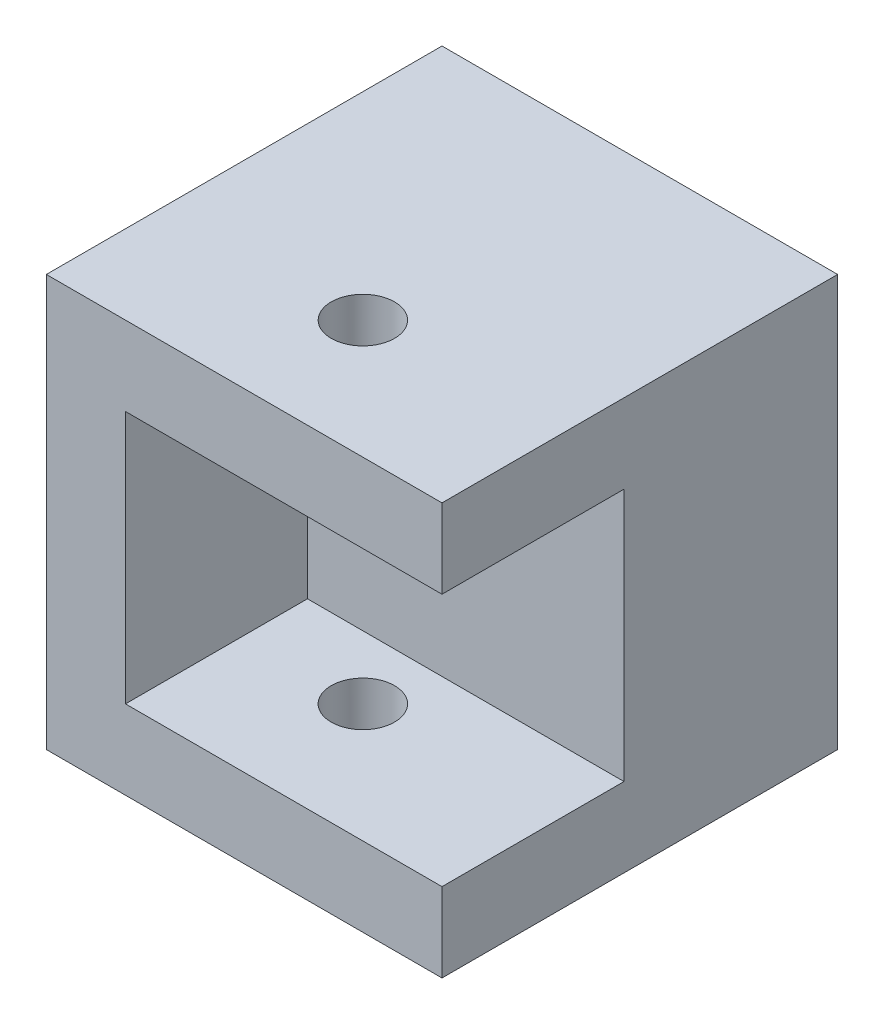
SolidWorks part; units mm, degrees
ref_plane "Front Plane" through (0, 0, 0) normal (0, 0, 1) x (1, 0, 0)
ref_plane "Top Plane" through (0, 0, 0) normal (0, 1, 0) x (1, 0, 0)
ref_plane "Right Plane" through (0, 0, 0) normal (1, 0, 0) x (0, 0, -1)
sketch "Sketch1" plane through (0, 0, 0) normal (0, 0, 1) x (1, 0, 0)
  line L0 (15.2003, 13.7604) -> (0.2003, 13.7604)
  line L1 (-4.7997, -6.2396) -> (0.2003, -6.2396)
  line L2 (-4.7997, -6.2396) -> (-4.7997, 19.7604)
  line L3 (-4.7997, 19.7604) -> (15.2003, 19.7604)
  line L4 (15.2003, 13.7604) -> (15.2003, 19.7604)
  line L5 (-4.7997, -6.2396) -> (15.2003, 19.7604) construction
  line L6 (-4.7997, 19.7604) -> (0, 0) construction
  line L7 (0.2003, 13.7604) -> (0.2003, -6.2396)
  point P0 (0, 0)
  dimension "D1" = 6
  dimension "D2" = 5
  dimension "D3" = 20
  dimension "D4" = 15
extrude "Boss-Extrude1" add sketch "Sketch1" along normal blind 25
sketch "Sketch2" plane through (-4.7997, 0, 0) normal (-1, 0, 0) x (0, 0, 1)
  line L0 (0, 19.7604) -> (4, 19.7604)
  line L1 (25, 19.7604) -> (0, 19.7604) construction
  line L2 (4, 19.7604) -> (4, -6.2396)
  line L3 (25, -6.2396) -> (0, -6.2396) construction
  line L4 (4, -6.2396) -> (0, -6.2396)
  line L5 (0, 19.7604) -> (0, -6.2396)
  dimension "D1" = 4
sketch "Sketch3" plane through (0, 13.7604, 0) normal (0, -1, 0) x (1, 0, 0)
  line L0 (0.2003, 25) -> (15.2003, 25) construction
  line L1 (15.2003, 25) -> (15.2003, 0) construction
  circle A0 centre (7.7003, 21.5) radius 2
  dimension "D1" = 4
  dimension "D2" = 3.5
  dimension "D3" = 7.5
extrude "Cut-Extrude1" cut sketch "Sketch3" against normal blind 15
extrude "Boss-Extrude2" add sketch "Sketch2" against normal up to surface (20 mm away) up to face at (15.2003, 16.7604, 12.5)
ref_plane "Plane1" through (0, 6.7604, 0) normal (0, 1, 0) x (1, 0, 0)
sketch "Sketch7" plane through (0, 0, 4) normal (0, 0, 1) x (1, 0, 0)
  line L0 (0.2003, -6.2396) -> (15.2003, -6.2396)
  line L1 (15.2003, 13.7604) -> (15.2003, -6.2396) construction
  line L2 (15.2003, -6.2396) -> (15.2003, -1.2396)
  line L3 (15.2003, -1.2396) -> (0.2003, -1.2396)
  line L4 (0.2003, -6.2396) -> (0.2003, 13.7604) construction
  line L5 (0.2003, -1.2396) -> (0.2003, -6.2396)
  dimension "D1" = 5
extrude "Boss-Extrude4" add sketch "Sketch7" along normal blind 25
sketch "Sketch8" plane through (15.2003, 0, 0) normal (1, 0, 0) x (0, 0, -1)
  line L0 (-4, -6.2396) -> (-4, 19.7604)
  line L8 (-25, 13.7604) -> (-4, 13.7604)
  line L9 (-4, 13.7604) -> (-4, -1.2396)
  line L10 (-4, -1.2396) -> (-29, -1.2396)
  line L11 (-25, 19.7604) -> (-25, 13.7604)
  line L12 (-29, -6.2396) -> (0, -6.2396)
  line L13 (0, -6.2396) -> (0, 19.7604)
  line L14 (0, 19.7604) -> (-25, 19.7604)
  line L15 (-29, -1.2396) -> (-29, -6.2396)
  line L17 (-4, 13.7604) -> (-4, -1.2396)
  line L18 (-29, -1.2396) -> (-29, -6.2396)
  line L20 (-4, -6.2396) -> (0, -6.2396)
  line L21 (0, -6.2396) -> (0, 19.7604)
  line L22 (0, 19.7604) -> (-4, 19.7604)
  line M10 (-4, 13.7604) -> (-4, -1.2396)
  line M13 (-29, -6.2396) -> (0, -6.2396)
  line M14 (0, -6.2396) -> (0, 19.7604)
  line M15 (0, 19.7604) -> (-25, 19.7604)
  dimension "D1" = 0
extrude "Cut-Extrude2" cut sketch "Sketch8" against normal up to surface (20 mm away) contours L0 M13 M14 M15 M10 up to face at (-4.7997, 6.7604, 12.5)
sketch "Sketch9" plane through (0, 0, 25) normal (0, 0, 1) x (1, 0, 0)
  line L7 (15.2003, 13.7604) -> (15.2003, 19.7604)
  line L8 (15.2003, 19.7604) -> (-4.7997, 19.7604)
  line L9 (-4.7997, 19.7604) -> (-4.7997, -6.2396)
  line L10 (-4.7997, -6.2396) -> (0.2003, -6.2396)
  line L11 (0.2003, -6.2396) -> (0.2003, -1.2396)
  line L12 (0.2003, -1.2396) -> (0.2003, 13.7604)
  line L13 (0.2003, 13.7604) -> (15.2003, 13.7604)
  line L14 (15.2003, 13.7604) -> (15.2003, 19.7604)
  line L15 (15.2003, 19.7604) -> (-4.7997, 19.7604)
  line L16 (-4.7997, 19.7604) -> (-4.7997, -6.2396)
  line L17 (-4.7997, -6.2396) -> (0.2003, -6.2396)
  line L18 (0.2003, -6.2396) -> (0.2003, -1.2396)
  line L19 (0.2003, -1.2396) -> (0.2003, 13.7604)
  line L20 (0.2003, 13.7604) -> (15.2003, 13.7604)
  dimension "D1" = 0
extrude "Boss-Extrude5" add sketch "Sketch9" along normal up to surface (4 mm away) up to face at (7.7003, -3.7396, 29)
sketch "Sketch10" plane through (0, -1.2396, 0) normal (0, 1, 0) x (1, 0, 0)
  circle A1 centre (7.7003, -21.5) radius 2 construction
  circle A3 centre (7.7003, -21.5) radius 2
extrude "Cut-Extrude3" cut sketch "Sketch10" against normal blind 10
sketch "Sketch11" plane through (0, 0, 4) normal (0, 0, -1) x (-1, 0, 0)
  line L0 (-0.2003, -1.2396) -> (-15.2003, -1.2396)
  line L1 (-15.2003, -1.2396) -> (-0.2003, -1.2396) construction
  line L2 (-15.2003, -1.2396) -> (-15.2003, 13.7604)
  line L3 (-15.2003, 13.7604) -> (-0.2003, 13.7604)
  line L4 (-0.2003, 13.7604) -> (-0.2003, -1.2396)
extrude "Boss-Extrude6" add sketch "Sketch11" against normal blind 14
sketch "Sketch14" plane through (0, 0, 18) normal (0, 0, 1) x (1, 0, 0)
  line L4 (0.2003, 13.7604) -> (0.2003, -1.2396)
  line L5 (0.2003, -1.2396) -> (15.2003, -1.2396)
  line L6 (15.2003, -1.2396) -> (15.2003, 13.7604)
  line L7 (15.2003, 13.7604) -> (0.2003, 13.7604)
  line L8 (0.2003, 13.7604) -> (0.2003, -1.2396)
  line L9 (0.2003, -1.2396) -> (15.2003, -1.2396)
  line L10 (15.2003, -1.2396) -> (15.2003, 13.7604)
  line L11 (15.2003, 13.7604) -> (0.2003, 13.7604)
  dimension "D1" = 0
extrude "Cut-Extrude5" cut sketch "Sketch14" against normal blind 0.5
sketch "Sketch16" plane through (15.2003, 0, 0) normal (1, 0, 0) x (0, 0, -1)
  line L8 (-29, 13.7604) -> (-17.5, 13.7604)
  line L9 (-17.5, 13.7604) -> (-17.5, -1.2396)
  line L10 (-17.5, -1.2396) -> (-29, -1.2396)
  line L11 (-29, -1.2396) -> (-29, -6.2396)
  line L12 (-29, -6.2396) -> (-4, -6.2396)
  line L13 (-4, -6.2396) -> (-4, 19.7604)
  line L14 (-4, 19.7604) -> (-29, 19.7604)
  line L15 (-29, 19.7604) -> (-29, 13.7604)
  line L16 (-29, 13.7604) -> (-17.5, 13.7604)
  line L17 (-17.5, 13.7604) -> (-17.5, -1.2396)
  line L18 (-17.5, -1.2396) -> (-29, -1.2396)
  line L19 (-29, -1.2396) -> (-29, -6.2396)
  line L20 (-29, -6.2396) -> (-4, -6.2396)
  line L21 (-4, -6.2396) -> (-4, 19.7604)
  line L22 (-4, 19.7604) -> (-29, 19.7604)
  line L23 (-29, 19.7604) -> (-29, 13.7604)
  dimension "D1" = 0
extrude "Boss-Extrude7" add sketch "Sketch16" along normal blind 5
sketch "Sketch13" plane through (0, 0, 4) normal (0, 0, -1) x (-1, 0, 0)
  line L0 (-20.2003, -6.2396) -> (4.7997, 19.7604) construction
  line L1 (-20.2003, 19.7604) -> (4.7997, -6.2396) construction
  line L3 (-0.7003, -0.2396) -> (-14.7003, -0.2396) construction
  line L4 (-0.7003, -0.2396) -> (-0.7003, 13.7604) construction
  line L5 (-0.7003, 13.7604) -> (-14.7003, 13.7604) construction
  line L6 (-14.7003, -0.2396) -> (-14.7003, 13.7604) construction
  circle A0 centre (-14.7003, -0.2396) radius 2
  circle A1 centre (-14.7003, 13.7604) radius 2
  circle A2 centre (-0.7003, 13.7604) radius 2
  circle A3 centre (-0.7003, -0.2396) radius 2
  point P8 (-7.7003, 6.7604)
  point P17 (-7.7003, 6.7604)
  point P22 (0, 0)
  point P23 (0, 0)
  dimension "D2" = 4
  dimension "D3" = 4
  dimension "D4" = 4
  dimension "D5" = 4
  dimension "D1" = 14
  dimension "D6" = 14
  dimension "D7" = 7
  dimension "D8" = 7
extrude "Cut-Extrude6" cut sketch "Sketch13" against normal blind 10
sketch "Sketch17" plane through (0, 13.7604, 0) normal (0, -1, 0) x (1, 0, 0)
  line L4 (0.2003, 29) -> (0.2003, 17.5)
  line L5 (0.2003, 17.5) -> (20.2003, 17.5)
  line L6 (20.2003, 17.5) -> (20.2003, 29)
  line L7 (20.2003, 29) -> (0.2003, 29)
  line L8 (0.2003, 29) -> (0.2003, 17.5)
  line L9 (0.2003, 17.5) -> (20.2003, 17.5)
  line L10 (20.2003, 17.5) -> (20.2003, 29)
  line L11 (20.2003, 29) -> (0.2003, 29)
  dimension "D1" = 0
extrude "Cut-Extrude7" cut sketch "Sketch17" against normal blind 1
